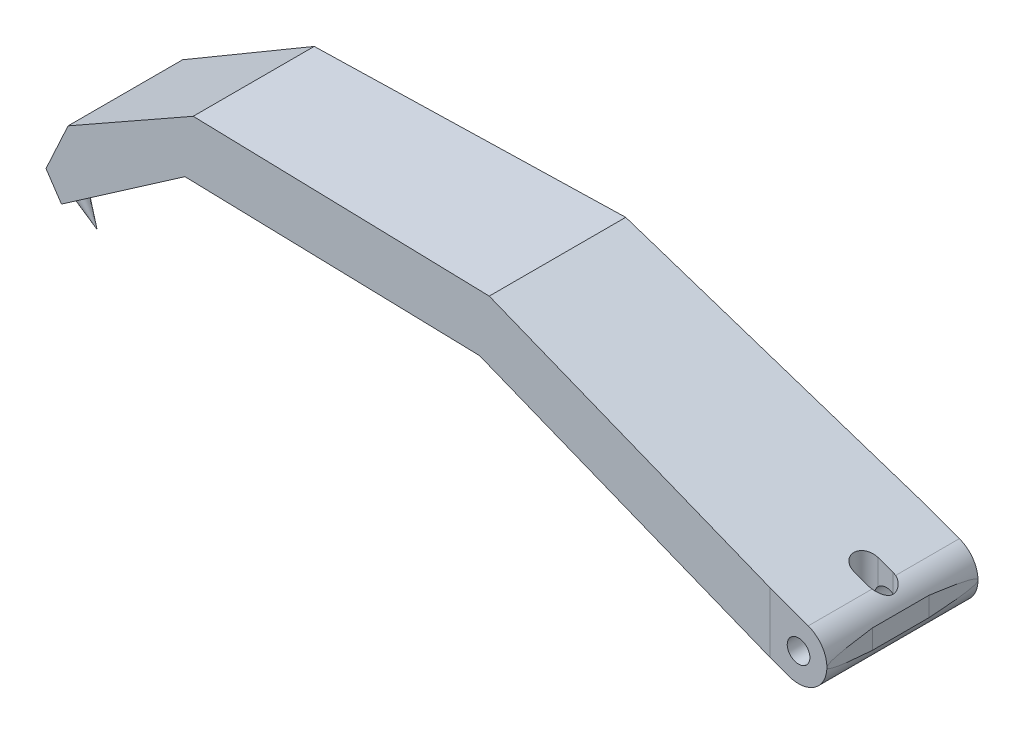
SolidWorks part; units mm, degrees
material "ABS"
ref_plane "Front Plane" through (0, 0, 0) normal (0, 0, 1) x (1, 0, 0)
ref_plane "Top Plane" through (0, 0, 0) normal (0, 1, 0) x (1, 0, 0)
ref_plane "Right Plane" through (0, 0, 0) normal (1, 0, 0) x (0, 0, -1)
sketch "Sketch3" plane through (0, 0, 0) normal (0, 0, 1) x (1, 0, 0)
  line L0 (1.2826, 3.5238) -> (-41.9063, 19.2433)
  line L1 (-41.9063, 19.2433) -> (-82.1095, 19.2433)
  line L2 (-82.1095, 19.2433) -> (-99.1006, 9.4335)
  line L3 (-99.1006, 9.4335) -> (-102.1006, 3)
  line L4 (-102.1006, 3) -> (-100, 0)
  line L5 (-100, 0) -> (-83.2288, 11.7433)
  line L6 (-83.2288, 11.7433) -> (-43.2288, 11.7433)
  line L7 (-43.2288, 11.7433) -> (-1.2826, -3.5238)
  line L8 (-1.2826, -3.5238) -> (1.2826, 3.5238) construction
  line L9 (-4.5939, -2.3186) -> (-2.0288, 4.7291) construction
  line L10 (-100, 0) -> (0, 0) construction
  line L17 (0, 0) -> (3.5238, -1.2826) construction
  circle A0 centre (0, 0) radius 1.5
  arc A3 (-1.2826, -3.5238) -> (1.2826, 3.5238) centre (0, 0) ccw
  point P14 (-3.75, 0)
  point P17 (0, 0)
  point P19 (0.0699, 0.192)
  dimension "D2" = 3
  dimension "D1" = 100
  dimension "D3" = 7.5
  dimension "D6" = 20
  dimension "D5" = 35
  dimension "D7" = 120
  dimension "D8" = 3
  dimension "D9" = 3
  dimension "D10" = 150
  dimension "D4" = 7.5
  dimension "D11" = 40
sketch "start-width" plane through (0, 0, 0) normal (1, 0, 0) x (0, 0, -1)
  line L0 (-10, 0) -> (10, 0)
  point P4 (0, 0)
  dimension "D1" = 20
ref_plane "Plane1" through (-102.1006, 0, 0) normal (1, 0, 0) x (0, 0, -1)
sketch "end-width" plane through (-102.1006, 0, 0) normal (1, 0, 0) x (0, 0, -1)
  line L0 (7.5, 0) -> (-7.5, 0)
  point P4 (0, 0)
  dimension "D1" = 15
sketch "picture-background" plane through (0, 0, 0) normal (0, 0, 1) x (1, 0, 0)
  line L0 (-153.9208, -162.5929) -> (-22.7793, -162.5929) construction
extrude "Boss-Extrude2" add sketch "Sketch3" along direction (0, 0, -1) on the side against the normal up to vertex (10 mm away) and the other way up to vertex (10 mm away)
sketch "Sketch12" plane through (0, 0, 0) normal (0, 1, 0) x (1, 0, 0)
  line L0 (-102.1006, 7.5) -> (-102.1006, -7.5) construction
  line L1 (-102.1006, 7.5) -> (-3.75, 7.5) construction
  line L2 (-102.1006, 7.5) -> (-102.1006, -7.5)
  line L3 (-3.75, -10) -> (-3.75, 10) construction
  line L4 (-102.1006, 7.5) -> (-3.75, 10) construction
  line L5 (-102.1006, -7.5) -> (-3.75, -10) construction
  line L6 (-102.1006, 0) -> (3.5238, 0) construction
  line L7 (0, -10) -> (0, 10) construction
  line L8 (0, -10) -> (0, 10) construction
  line L9 (-102.1006, 7.5) -> (-3.75, 10)
  line L12 (-102.1006, -7.5) -> (-3.75, -10)
  line L13 (1.2826, 10) -> (-41.9063, 10) construction
  line L14 (3.5238, -3.75) -> (3.75, -10)
  line L15 (-1.0762, 0) -> (0.9238, 0) construction
  line L16 (-1.0762, 1.6) -> (0.9238, 1.6)
  line L17 (3.75, 10) -> (-3.75, 10)
  line L18 (-3.75, -10) -> (3.75, -10)
  line L19 (3.5238, -3.75) -> (3.5238, 3.75)
  line L21 (0, 0) -> (3.5238, 0) construction
  line L22 (3.5238, 3.75) -> (3.75, 10)
  line L23 (-1.0762, -1.6) -> (0.9238, -1.6)
  line L28 (0, 0) -> (3.5238, 0)
  arc A0 (-1.0762, 1.6) -> (-1.0762, -1.6) centre (-1.0762, 0) ccw
  arc A1 (0.9238, -1.6) -> (0.9238, 1.6) centre (0.9238, 0) ccw
  point P17 (-0.0762, 0)
  point P25 (22.9424, 1.6)
  point P26 (3.5238, 0)
  point P27 (3.5238, 0)
  point P30 (24.0835, 0)
  dimension "D3" = 1.6
  dimension "D4" = 2
  dimension "D5" = 2.6
  dimension "D1" = 3.75
  dimension "D2" = 7.5
extrude "top-form" cut sketch "Sketch12" along normal through all and the other way through all flip side to cut contours L19 L22 L17 L9 L2 L12 L18 L14 A1 L23 A0 L16
sketch "Sketch17" plane through (-32.899, 46.9846, 0) normal (0.5736, -0.8192, 0) x (0.8192, 0.5736, 0)
  line L0 (-81.9152, 0) -> (-61.4413, 0) construction
  line L1 (-81.9152, -7.5534) -> (-81.9152, 7.5534) construction
  line L2 (-61.4413, -7.9797) -> (-61.4413, 7.9797) construction
  line L4 (-81.9152, -7.5534) -> (-61.4413, -7.9797) construction
  circle A0 centre (-80.4152, 6.0843) radius 0.75
  circle A1 centre (-80.4152, -6.0843) radius 0.75
  dimension "D1" = 1.5
  dimension "D2" = 1.5
  dimension "D3" = 1.5
extrude "spikes" add sketch "Sketch17" along normal blind 6 draft 12
equation "\"D4@Sketch3\"=\"D3@Sketch3\""
